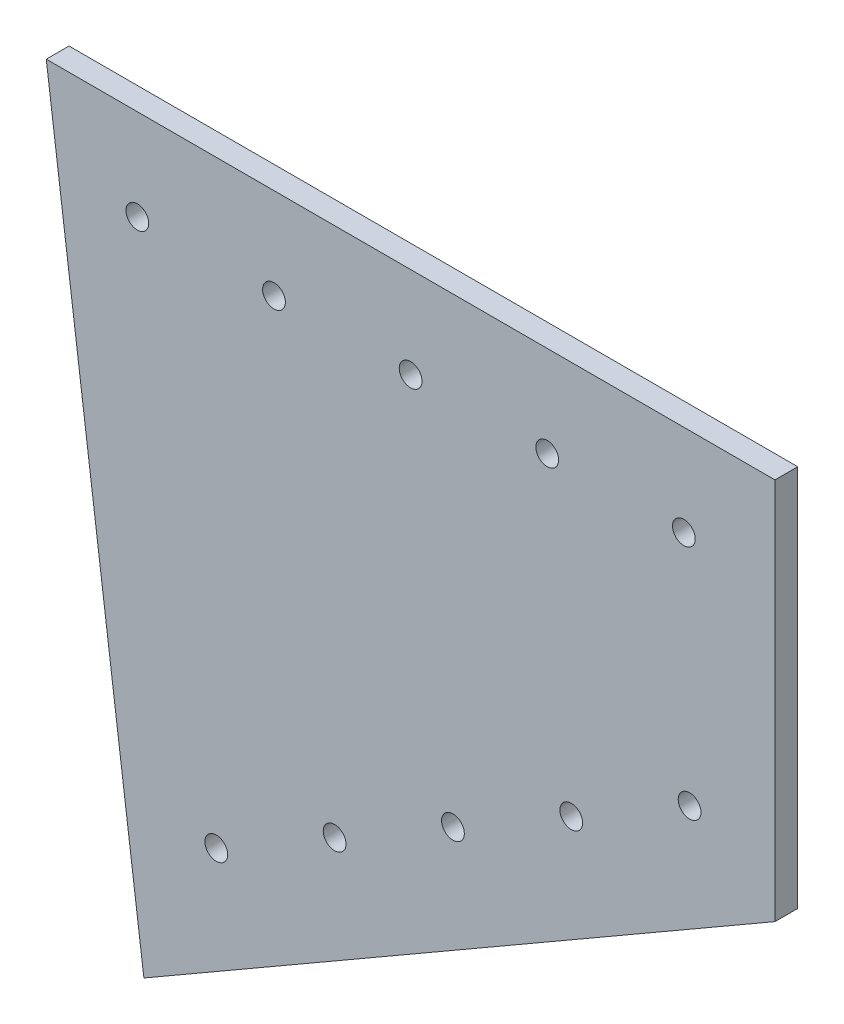
SolidWorks part; units mm, degrees
ref_plane "Front Plane" through (0, 0, 0) normal (0, 0, 1) x (1, 0, 0)
ref_plane "Top Plane" through (0, 0, 0) normal (0, 1, 0) x (1, 0, 0)
ref_plane "Right Plane" through (0, 0, 0) normal (1, 0, 0) x (0, 0, -1)
sketch "Sketch1" plane through (0, 0, 0) normal (0, 0, 1) x (1, 0, 0)
  line L0 (0, 0) -> (0, 53.34)
  line L1 (0, 53.34) -> (-101.6, 53.34)
  line L2 (0, 0) -> (-87.9882, -50.8)
  line L3 (-87.9882, -50.8) -> (-101.6, 53.34)
  dimension "D1" = 53.34
  dimension "D2" = 101.6
  dimension "D3" = 101.6
  dimension "D4" = 30
extrude "Boss-Extrude1" add sketch "Sketch1" along normal blind 3.175
sketch "Sketch2" plane through (0, 0, 0) normal (0, 0, -1) x (-1, 0, 0)
  line L0 (0, 40.64) -> (12.7, 40.64) construction
  line L1 (0, 0) -> (0, 53.34) construction
  line L2 (12.7, 40.64) -> (12.7, 53.34) construction
  line L3 (0, 53.34) -> (101.6, 53.34) construction
  line L4 (11.9039, 8.026) -> (5.4526, -3.148) construction
  line L6 (87.9882, -50.8) -> (0, 0) construction
  line L7 (11.9039, 8.026) -> (28.4017, -1.499) construction
  line L8 (11.9039, 8.026) -> (0, 14.8987) construction
  line L9 (77.895, -30.074) -> (89.7989, -36.9467) construction
  line L10 (101.6, 53.34) -> (87.9882, -50.8) construction
  circle A0 centre (12.7, 40.64) radius 1.5875
  circle A1 centre (31.75, 40.64) radius 1.5875
  circle A2 centre (50.8, 40.64) radius 1.5875
  circle A3 centre (69.85, 40.64) radius 1.5875
  circle A4 centre (88.9, 40.64) radius 1.5875
  circle A5 centre (11.9039, 8.026) radius 1.5875
  circle A6 centre (28.4017, -1.499) radius 1.5875
  circle A7 centre (44.8994, -11.024) radius 1.5875
  circle A8 centre (61.3972, -20.549) radius 1.5875
  circle A9 centre (77.895, -30.074) radius 1.5875
  dimension "D2" = 3.175
  dimension "D5" = 3.175
  dimension "D1" = 12.7
  dimension "D3" = 5
  dimension "D6" = 5
extrude "Cut-Extrude1" cut sketch "Sketch2" against normal up to next
